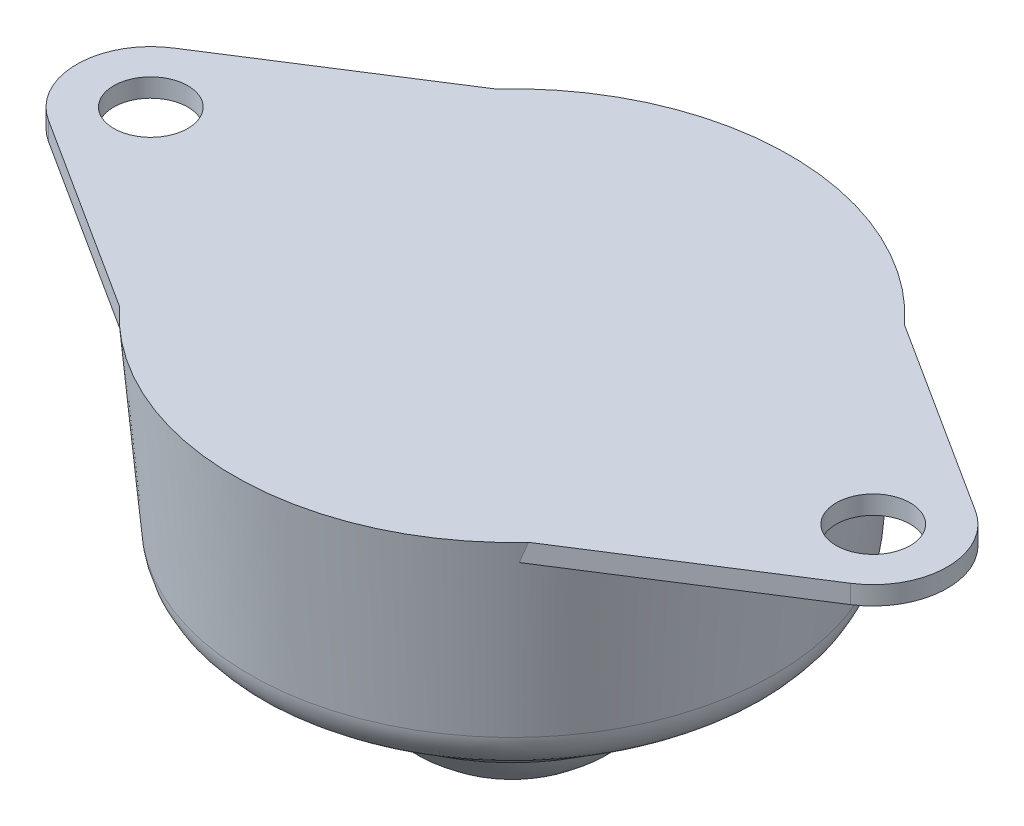
SolidWorks part; units mm, degrees
ref_plane "Front Plane" through (0, 0, 0) normal (0, 0, 1) x (1, 0, 0)
ref_plane "Top Plane" through (0, 0, 0) normal (0, 1, 0) x (1, 0, 0)
ref_plane "Right Plane" through (0, 0, 0) normal (1, 0, 0) x (0, 0, -1)
sketch "Sketch1" plane through (0, 0, 0) normal (0, 1, 0) x (1, 0, 0)
  line L0 (-19.5, 0) -> (19.5, 0) construction
  line L1 (-7.8077, 12.2184) -> (-21.6538, 3.3706)
  line L2 (7.8077, 12.2184) -> (21.6538, 3.3706)
  line L4 (21.6538, -3.3706) -> (7.8077, -12.2184)
  line L6 (-21.6538, -3.3706) -> (-7.8077, -12.2184)
  circle A0 centre (19.5, 0) radius 2
  circle A1 centre (-19.5, 0) radius 2
  circle A2 centre (0, 0) radius 12.5
  circle A3 centre (-19.5, 0) radius 4
  circle A4 centre (0, 0) radius 14.5
  circle A5 centre (19.5, 0) radius 4
  point P4 (0, 0)
  point P17 (23.5, 0)
  point P21 (-23.5, 0)
  point P22 (-21.5, 0)
  point P23 (21.5, 0)
  dimension "D2" = 4
  dimension "D3" = 25
  dimension "D1" = 43
  dimension "D5" = 47
  dimension "D6" = 39
  dimension "D4" = 2
sketch "Sketch2" plane through (0, 0, 0) normal (0, 0, 1) x (1, 0, 0)
  line L0 (0, 0) -> (0, -20) construction
  line L1 (-7.0711, -15) -> (-9, -15)
  line L2 (-9, -15) -> (-10.7321, -12)
  line L3 (-10.7321, -12) -> (-13.9501, -12)
  line L4 (-13.9501, -12) -> (-15, 0)
  line L5 (-7.3079, -15) -> (-7.1311, -14.8232)
  line L6 (-19.5, 0) -> (19.5, 0) construction
  line L7 (-15, 0) -> (0, 0)
  circle A0 centre (0, -12.5) radius 7.5
  dimension "D1" = 20
  dimension "D2" = 5
  dimension "D7" = 15
  dimension "D3" = 85
  dimension "D4" = 60
  dimension "D5" = 15
  dimension "D6" = 12
  dimension "D8" = 9
  dimension "D9" = 45
  dimension "D10" = 0.25
revolve "Revolve1" add sketch "Sketch2" angle 360 about L0
fillet "Fillet1" radius 2.5 2 edges at (-9, -15, 0) (-13.9501, -12, 0)
extrude "Boss-Extrude1" add sketch "Sketch1" against normal blind 1
fillet "Fillet2" radius 0.25 1 edges at (-7.3079, -15, 0)
